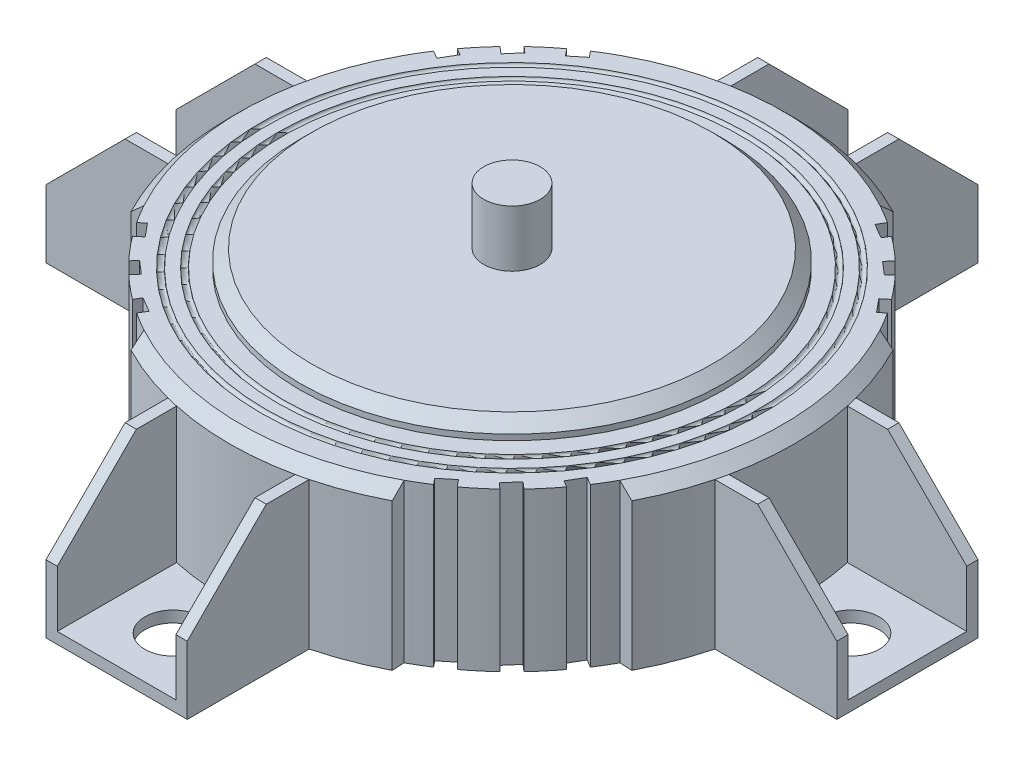
SolidWorks part; units mm, degrees
material "6061 Alloy"
ref_plane "Front Plane" through (0, 0, 0) normal (0, 0, 1) x (1, 0, 0)
ref_plane "Top Plane" through (0, 0, 0) normal (0, 1, 0) x (1, 0, 0)
ref_plane "Right Plane" through (0, 0, 0) normal (1, 0, 0) x (0, 0, -1)
sketch "Sketch1" plane through (0, 0, 0) normal (0, 0, 1) x (1, 0, 0)
  line L0 (0, 0) -> (0, 41) construction
  line L1 (0, 0) -> (-50, 0)
  line L2 (-50, 0) -> (-50, 28)
  line L3 (-50, 28) -> (-37.5, 28)
  line L4 (-37.5, 28) -> (-37.5, 31)
  line L5 (-37.5, 31) -> (-5, 31)
  line L6 (-5, 31) -> (-5, 41)
  line L7 (-5, 41) -> (0, 41)
  line L8 (0, 0) -> (0, 41)
  dimension "D1" = 100
  dimension "D2" = 75
  dimension "D3" = 10
  dimension "D4" = 10
  dimension "D5" = 3
  dimension "D6" = 28
revolve "Revolve1" add sketch "Sketch1" angle 360 about L0
chamfer "Chamfer1" distance 2 angle 45 2 edges at (0, 31, -37.5) (0, 28, -50)
sketch "Sketch2" plane through (0, 0, 0) normal (0, 0, 1) x (1, 0, 0)
  line L0 (0, 0) -> (0, 26) construction
  line L1 (50, 26) -> (-50, 26) construction
  line L2 (-10.5, 26) -> (-12.5, 26)
  line L3 (-12.5, 26) -> (-12.5, 0)
  line L4 (-50, 0) -> (50, 0) construction
  line L5 (-12.5, 0) -> (12.5, 0)
  line L6 (-10.5, 26) -> (-10.5, 2)
  line L7 (-10.5, 2) -> (10.5, 2)
  line L8 (10.5, 26) -> (10.5, 2)
  line L9 (10.5, 26) -> (12.5, 26)
  line L10 (12.5, 26) -> (12.5, 0)
  point P16 (0, 2)
  dimension "D1" = 2
  dimension "D2" = 2
  dimension "D3" = 25
extrude "Boss-Extrude1" add sketch "Sketch2" along normal blind 70
chamfer "Chamfer2" distance 14 angle 45 2 edges at (-11.5, 26, 70) (11.5, 26, 70)
sketch "Sketch3" plane through (0, 0, 0) normal (0, 1, 0) x (1, 0, 0)
  line L0 (0, -60) -> (0, 0) construction
  circle A0 centre (0, -60) radius 5
  dimension "D2" = 10
  dimension "D1" = 60
extrude "Cut-Extrude1" cut sketch "Sketch3" along normal blind 70
pattern_circular "CirPattern1" count 4 over 360 about axis through (0, 0, 0) along (0, 1, 0) of "Cut-Extrude1", "Chamfer2", "Boss-Extrude1"
sketch "Sketch4" plane through (0, 0, 0) normal (0, 1, 0) x (1, 0, 0)
  line L0 (0, 0) -> (35.3553, -35.3553) construction
  line L1 (42.117, -23.0251) -> (44.3334, -23.1202)
  line L2 (23.0251, -42.117) -> (23.1202, -44.3334)
  arc A0 (12.5, -48.4123) -> (48.4123, -12.5) centre (0, 0) ccw construction
  circle A1 centre (0, 0) radius 48 construction
  arc A2 (23.1202, -44.3334) -> (44.3334, -23.1202) centre (0, 0) ccw
  arc A3 (23.0251, -42.117) -> (42.117, -23.0251) centre (0, 0) ccw
  dimension "D1" = 30
  dimension "D2" = 27
extrude "Cut-Extrude3" cut sketch "Sketch4" along normal blind 70
sketch "Sketch5" plane through (0, 0, 0) normal (0, 1, 0) x (1, 0, 0)
  line L0 (0, 0) -> (33.9411, -33.9411) construction
  line L1 (34.1047, -36.0561) -> (31.8261, -34.1047)
  line L2 (34.1047, -36.0561) -> (36.0561, -33.7776)
  line L3 (31.8261, -34.1047) -> (33.7776, -31.8261)
  line L4 (36.0561, -33.7776) -> (33.7776, -31.8261)
  line L5 (34.1047, -36.0561) -> (33.7776, -31.8261) construction
  line L6 (31.8261, -34.1047) -> (36.0561, -33.7776) construction
  arc A0 (23.0251, -42.117) -> (42.117, -23.0251) centre (0, 0) ccw construction
  dimension "D1" = 3
  dimension "D2" = 3
extrude "Cut-Extrude4" cut sketch "Sketch5" along normal blind 70
pattern_circular "CirPattern2" count 2 every 10 about axis through (0, 0, 0) along (0, 1, 0) of "Cut-Extrude4"
pattern_circular "CirPattern3" count 4 over 360 about axis through (0, 0, 0) along (0, 1, 0) of "Cut-Extrude3", "CirPattern2", "Cut-Extrude4"
sketch "Sketch9" plane through (0, 28, 0) normal (0, 1, 0) x (1, 0, 0)
  circle A0 centre (0, 0) radius 41
  dimension "D1" = 82
sketch "Sketch10" plane through (0, 28, 0) normal (0, 1, 0) x (1, 0, 0)
  circle A0 centre (0, 0) radius 44
  dimension "D1" = 88
sweep "Cut-Sweep1" cut path "Sketch9" circular profile diameter 1 parameters "D3"=1
sweep "Cut-Sweep2" cut path "Sketch10" circular profile diameter 1 parameters "D3"=1
sketch "Sketch41" plane through (0, 0, 0) normal (0, -1, 0) x (1, 0, 0)
  circle A0 centre (0, 0) radius 37.5
  dimension "D1" = 75
extrude "Cut-Extrude5" cut sketch "Sketch41" against normal blind 10
